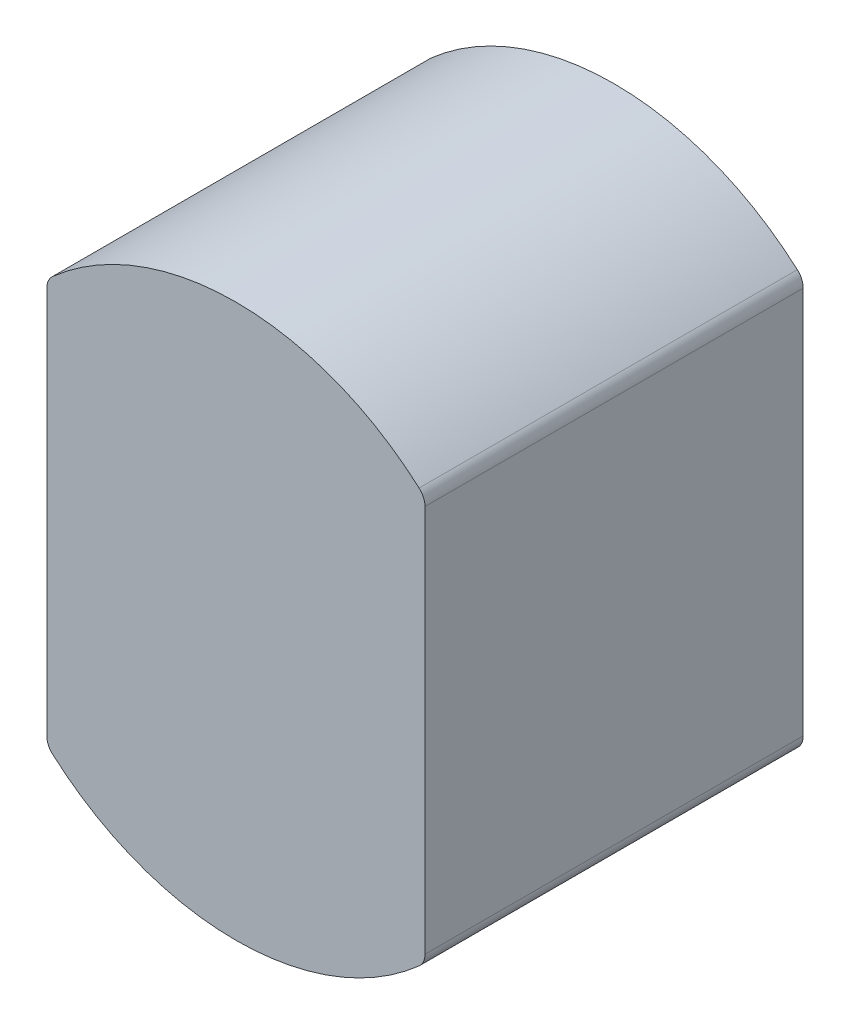
SolidWorks part; units mm, degrees
ref_plane "Спереди" through (0, 0, 0) normal (0, 0, 1) x (1, 0, 0)
ref_plane "Сверху" through (0, 0, 0) normal (0, 1, 0) x (1, 0, 0)
ref_plane "Справа" through (0, 0, 0) normal (1, 0, 0) x (0, 0, -1)
sketch "Эскиз1" plane through (0, 0, 0) normal (0, 0, 1) x (1, 0, 0)
  line L10 (32.5, -34.641) -> (-32.5, -34.641)
  line L11 (32.5, -34.641) -> (32.5, 34.641)
  line L12 (32.5, 34.641) -> (-32.5, 34.641)
  line L13 (-32.5, -34.641) -> (-32.5, 34.641)
  line L14 (32.5, -34.641) -> (-32.5, 34.641) construction
  line L15 (32.5, 34.641) -> (-32.5, -34.641) construction
  circle A1 centre (0, 0) radius 47.5
  dimension "D1" = 65
  dimension "D2" = 95
extrude "Бобышка-Вытянуть1" add sketch "Эскиз1" along normal blind 65 contours L12 A1 | L13 L10 L11 L12 | L10 A1
fillet "Скругление2" radius 3 4 edges at (32.5, 34.641, 32.5) (32.5, -34.641, 32.5) (-32.5, -34.641, 32.5) (-32.5, 34.641, 32.5)
